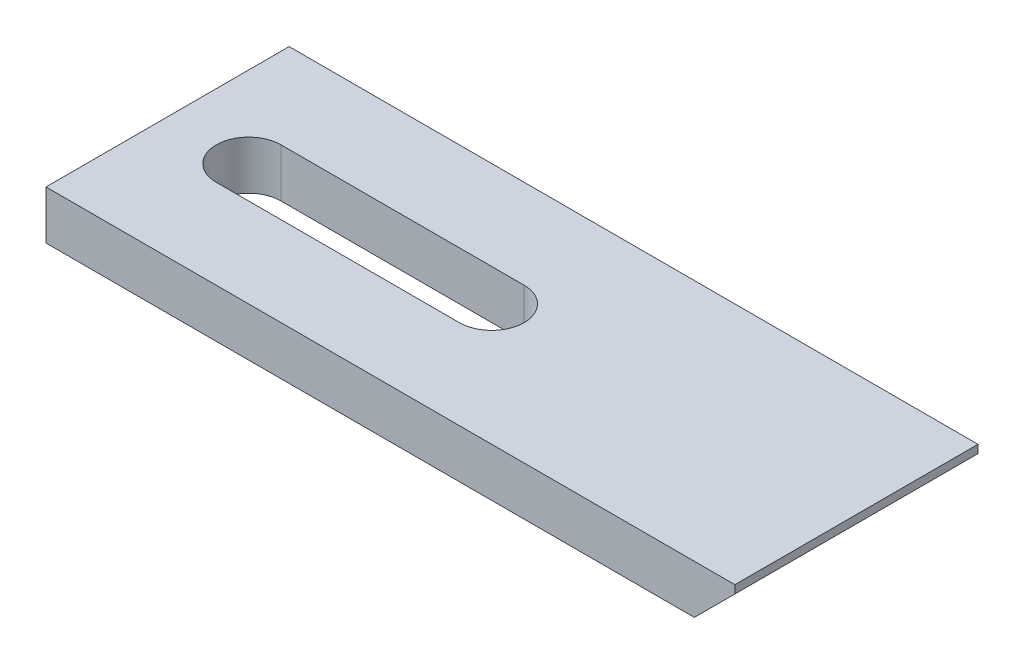
SolidWorks part; units mm, degrees
material "AISI 321 Отожженная нержавеющая сталь (SS)"
ref_plane "Спереди" through (0, 0, 0) normal (0, 0, 1) x (1, 0, 0)
ref_plane "Сверху" through (0, 0, 0) normal (0, 1, 0) x (1, 0, 0)
ref_plane "Справа" through (0, 0, 0) normal (1, 0, 0) x (0, 0, -1)
sketch "Эскиз1" plane through (0, 0, 0) normal (0, 1, 0) x (1, 0, 0)
  line L0 (-42.5, -15) -> (42.5, 15) construction
  line L1 (-42.5, 15) -> (42.5, 15)
  line L2 (-42.5, 15) -> (-42.5, -15)
  line L3 (-42.5, -15) -> (42.5, -15)
  line L4 (42.5, 15) -> (42.5, -15)
  line L5 (-32.5, 0) -> (-42.5, 0) construction
  line L6 (-32.5, 4) -> (-22.5, 4)
  line L7 (-32.5, -4) -> (-22.5, -4)
  line L8 (-17.5, 15) -> (-17.5, -15) construction
  line L9 (-2.5, 4) -> (-12.5, 4)
  line L10 (-2.5, -4) -> (-12.5, -4)
  arc A0 (-32.5, 4) -> (-32.5, -4) centre (-32.5, 0) ccw
  arc A1 (-22.5, -4) -> (-22.5, 4) centre (-22.5, 0) ccw
  arc A2 (-12.5, -4) -> (-12.5, 4) centre (-12.5, 0) cw
  arc A3 (-2.5, 4) -> (-2.5, -4) centre (-2.5, 0) cw
  dimension "D3" = 8
  dimension "D6" = 20
  dimension "D1" = 85
  dimension "D2" = 30
  dimension "D4" = 10
  dimension "D5" = 10
extrude "Бобышка-Вытянуть1" add sketch "Эскиз1" along normal blind 6
sketch "Эскиз2" plane through (0, 0, 15) normal (0, 0, 1) x (1, 0, 0)
  line L0 (42.5, 5) -> (37.5, 0)
  line L1 (42.5, 6) -> (42.5, 0) construction
  line L2 (-42.5, 0) -> (42.5, 0) construction
  line L3 (37.5, 0) -> (42.5, 0)
  line L4 (42.5, 0) -> (42.5, 5)
  dimension "D1" = 5
extrude "Вырез-Вытянуть1" cut sketch "Эскиз2" against normal through all
ref_plane "Плоскость1" through (-2.5, 0, 0) normal (-1, 0, 0) x (0, 0, 1)
sketch "Эскиз3" plane through (0, 6, 0) normal (0, 1, 0) x (1, 0, 0)
  line L0 (-2.5, 4) -> (-12.5, 4) construction
  line L1 (-22.5, -4) -> (-12.5, -4)
  line L2 (-22.5, -4) -> (-22.5, 4)
  line L3 (-22.5, 4) -> (-12.5, 4)
  line L4 (-12.5, -4) -> (-12.5, 4)
  arc A0 (-12.5, 4) -> (-12.5, -4) centre (-12.5, 0) ccw construction
extrude "Вырез-Вытянуть2" cut sketch "Эскиз3" against normal through all
